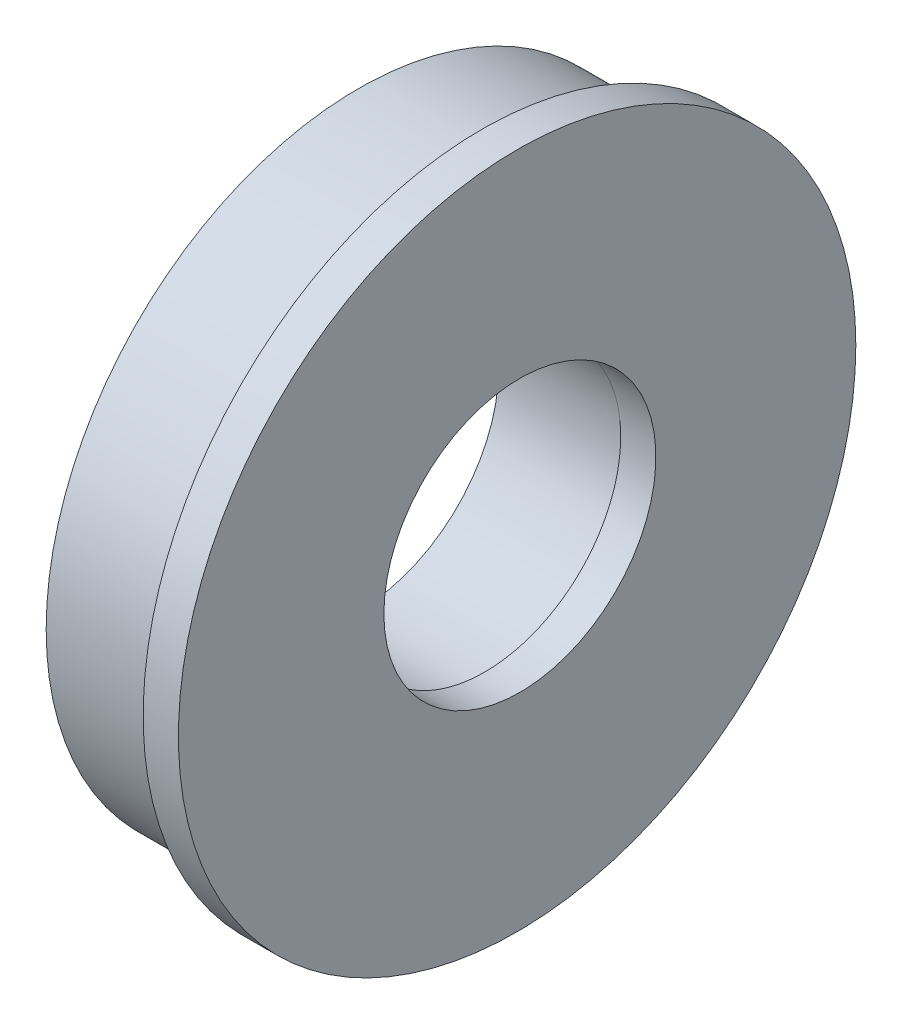
SolidWorks part; units mm, degrees
ref_plane "Front Plane" through (0, 0, 0) normal (0, 0, 1) x (1, 0, 0)
ref_plane "Top Plane" through (0, 0, 0) normal (0, 1, 0) x (1, 0, 0)
ref_plane "Right Plane" through (0, 0, 0) normal (1, 0, 0) x (0, 0, -1)
sketch "Sketch2" plane through (0, 0, 0) normal (1, 0, 0) x (0, 0, -1)
  circle A0 centre (-373.3141, 282.6904) radius 15.9152
  circle A1 centre (-373.3141, 282.6904) radius 35.421
extrude "Boss-Extrude1" add sketch "Sketch2" along normal blind 14
sketch "Sketch3" plane through (14, 0, 0) normal (1, 0, 0) x (0, 0, -1)
  circle A2 centre (-373.3141, 282.6904) radius 38.421
  circle A3 centre (-373.3141, 282.6904) radius 38.421
  dimension "D1" = 3
extrude "Boss-Extrude2" add sketch "Sketch3" along normal blind 4
sketch "Sketch4" plane through (14, 0, 0) normal (-1, 0, 0) x (0, 0, 1)
  circle A0 centre (372.9998, 283.0614) radius 15.4289
extrude "Cut-Extrude1" cut sketch "Sketch4" against normal blind 4
